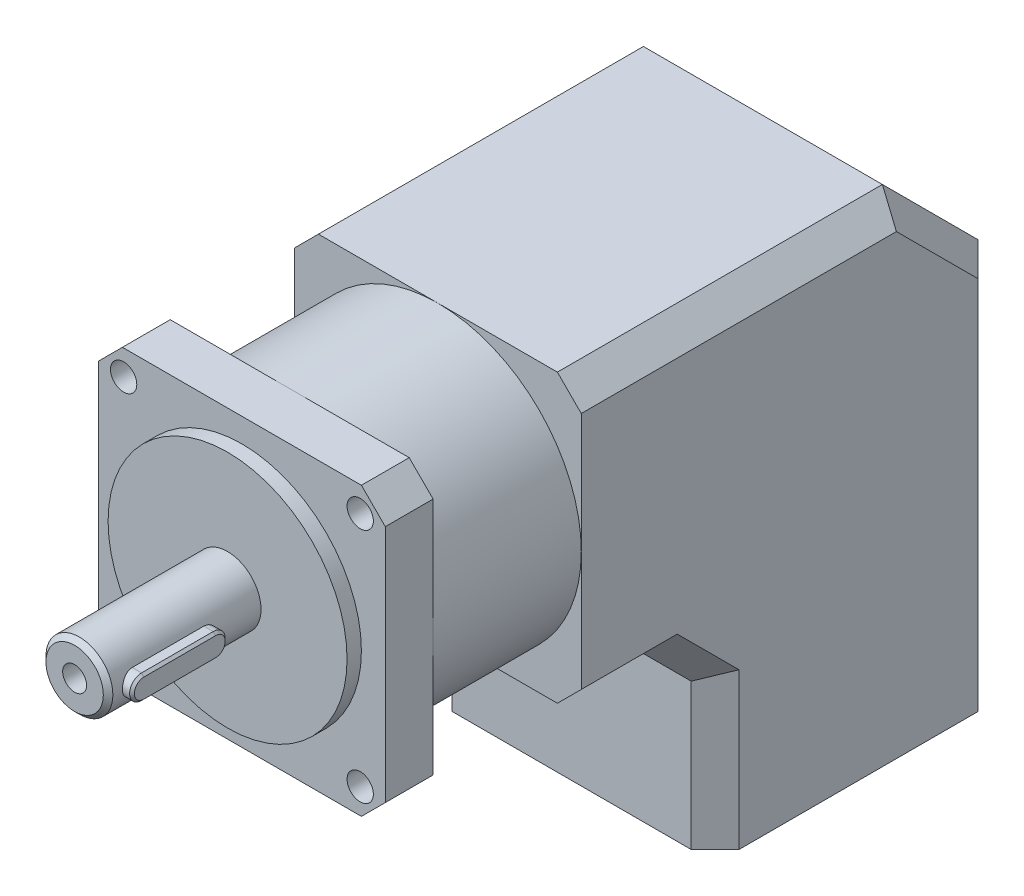
SolidWorks part; units mm, degrees
material "0.6010 (EN-GJL-100)"
ref_plane "前视基准面" through (0, 0, 0) normal (0, 0, 1) x (1, 0, 0)
ref_plane "上视基准面" through (0, 0, 0) normal (0, 1, 0) x (1, 0, 0)
ref_plane "右视基准面" through (0, 0, 0) normal (1, 0, 0) x (0, 0, -1)
sketch "草图1" plane through (0, 0, 0) normal (1, 0, 0) x (0, 0, -1)
  line L0 (0, 0) -> (0, -40.5)
  line L1 (60, -40.5) -> (60, 40)
  line L2 (60, 40) -> (40, 60)
  line L3 (40, 60) -> (-28, 60)
  line L4 (-28, 60) -> (-28, 0)
  line L5 (-28, 0) -> (0, 0)
  line L6 (0, -40.5) -> (60, -40.5)
  line L7 (30, -40.5) -> (30, 90.6728) construction
  point P12 (30, -40.5)
  dimension "D1" = 60
  dimension "D2" = 100.5
  dimension "D3" = 88
  dimension "D4" = 135
  dimension "D5" = 40.5
  dimension "D6" = 20
extrude "凸台-拉伸1" add sketch "草图1" along normal mid plane 60
chamfer "倒角1" distance 10 angle 45 1 edges at (0, 0, 0)
chamfer "倒角2" distance 5 angle 45 12 edges at (-30, 60, -6) (-30, 50, -50) (-30, -0.25, -60) (30, 60, -6) (30, 50, -50) (30, -0.25, -60) (-30, -25.25, 0) (-30, -5, 5) (-30, 0, 19) (30, 0, 19) (30, -5, 5) (30, -25.25, 0)
sketch "草图2" plane through (0, 0, 28) normal (0, 0, 1) x (1, 0, 0)
  line L0 (-30, 30) -> (30, 30) construction
  line L1 (-30, 55) -> (-30, 5) construction
  line L2 (30, 55) -> (30, 5) construction
  circle A0 centre (0, 30) radius 30
extrude "凸台-拉伸2" add sketch "草图2" along normal blind 41
sketch "草图3" plane through (0, 0, 69) normal (0, 0, 1) x (1, 0, 0)
  line L0 (-30, 30) -> (-30, 5) construction
  line L1 (-30, 5) -> (-25, 0) construction
  line L6 (-25, 0) -> (25, 0) construction
  line L7 (25, 0) -> (30, 5) construction
  line L8 (30, 55) -> (30, 30) construction
  line L9 (30, 55) -> (25, 60) construction
  line L10 (25, 60) -> (0, 60) construction
  line L11 (0, 60) -> (-25, 60) construction
  line L12 (-25, 60) -> (-30, 55) construction
  line L13 (-30, 55) -> (-30, 30) construction
  line L14 (-30, 30) -> (-30, 5)
  line L15 (-30, 5) -> (-25, 0)
  line L16 (-25, 0) -> (25, 0)
  line L17 (25, 0) -> (30, 5)
  line L18 (30, 55) -> (30, 30)
  line L19 (30, 55) -> (25, 60)
  line L20 (25, 60) -> (0, 60)
  line L21 (0, 60) -> (-25, 60)
  line L22 (-25, 60) -> (-30, 55)
  line L23 (-30, 55) -> (-30, 30)
  line L24 (30, 30) -> (30, 5) construction
  line L25 (30, 30) -> (30, 5)
extrude "凸台-拉伸3" add sketch "草图3" against normal blind 10
sketch "草图4" plane through (0, 0, 69) normal (0, 0, 1) x (1, 0, 0)
  circle A0 centre (0, 30) radius 25
  dimension "D1" = 50
extrude "凸台-拉伸4" add sketch "草图4" along normal blind 3
sketch "草图5" plane through (0, 0, 69) normal (0, 0, 1) x (1, 0, 0)
  circle A0 centre (0, 30) radius 7
  dimension "D1" = 14
extrude "凸台-拉伸5" add sketch "草图5" along normal blind 35
sketch "草图6" plane through (0, 0, 69) normal (0, 0, 1) x (1, 0, 0)
  line L0 (-27.5, 57.5) -> (27.5, 2.5) construction
  line L1 (-25, 60) -> (-30, 55) construction
  line L2 (25, 0) -> (30, 5) construction
  circle A0 centre (0, 30) radius 35 construction
  circle A1 centre (-24.7487, 54.7487) radius 2.75
  circle A2 centre (24.7487, 54.7487) radius 2.75
  circle A3 centre (24.7487, 5.2513) radius 2.75
  circle A4 centre (-24.7487, 5.2513) radius 2.75
  dimension "D1" = 70
  dimension "D2" = 5.5
  dimension "D3" = 4
extrude "切除-拉伸1" cut sketch "草图6" against normal up to next
sketch "草图8" plane through (0, -40.5, 0) normal (0, -1, 0) x (1, 0, 0)
  line L0 (30, -5) -> (30, -55) construction
  circle A0 centre (0, -30) radius 25
  point P7 (30, -30)
  dimension "D1" = 50
extrude "切除-拉伸2" cut sketch "草图8" against normal blind 5
sketch "草图9" plane through (0, -40.5, 0) normal (0, -1, 0) x (1, 0, 0)
  circle A0 centre (0, -30) radius 7
  dimension "D1" = 14
extrude "切除-拉伸3" cut sketch "草图9" against normal blind 31.5
sketch "草图10" plane through (0, 0, 0) normal (1, 0, 0) x (0, 0, -1)
  line L0 (-98.5, 30) -> (-83.5, 30) construction
  line L1 (-98.5, 32.5) -> (-83.5, 32.5)
  line L2 (-98.5, 27.5) -> (-83.5, 27.5)
  line L3 (-104, 37) -> (-104, 23) construction
  line L4 (-72, 55) -> (-72, 5) construction
  line L5 (-72, 55) -> (-72, 5) construction
  arc A0 (-98.5, 32.5) -> (-98.5, 27.5) centre (-98.5, 30) ccw
  arc A1 (-83.5, 27.5) -> (-83.5, 32.5) centre (-83.5, 30) ccw
  point P2 (-91, 30)
  point P7 (-101, 30)
  point P10 (-81, 30)
  point P13 (-72, 30)
  dimension "D1" = 5
  dimension "D2" = 3
  dimension "D3" = 20
extrude "凸台-拉伸6" add sketch "草图10" along normal blind 9
chamfer "倒角3" distance 0.5 angle 45 4 edges at (9, 27.5, 91) (9, 30, 81) (9, 30, 101) (9, 32.5, 91)
sketch "草图11" plane through (0, -40.5, 0) normal (0, -1, 0) x (1, 0, 0)
  line L0 (-27.5, -2.5) -> (27.5, -57.5) construction
  line L1 (-25, 0) -> (-30, -5) construction
  line L2 (25, -60) -> (30, -55) construction
  circle A0 centre (0, -30) radius 35 construction
  circle A1 centre (-24.7487, -5.2513) radius 2
  circle A2 centre (24.7487, -5.2513) radius 2
  circle A3 centre (24.7487, -54.7487) radius 2
  circle A4 centre (-24.7487, -54.7487) radius 2
  dimension "D1" = 70
  dimension "D2" = 4
  dimension "D3" = 4
extrude "切除-拉伸4" cut sketch "草图11" against normal blind 30
sketch "草图12" plane through (0, 0, 104) normal (0, 0, 1) x (1, 0, 0)
  circle A0 centre (0, 30) radius 2.5
  dimension "D1" = 5
extrude "切除-拉伸5" cut sketch "草图12" against normal blind 30
chamfer "倒角4" distance 1 angle 45 1 edges at (7, 30, 104)
